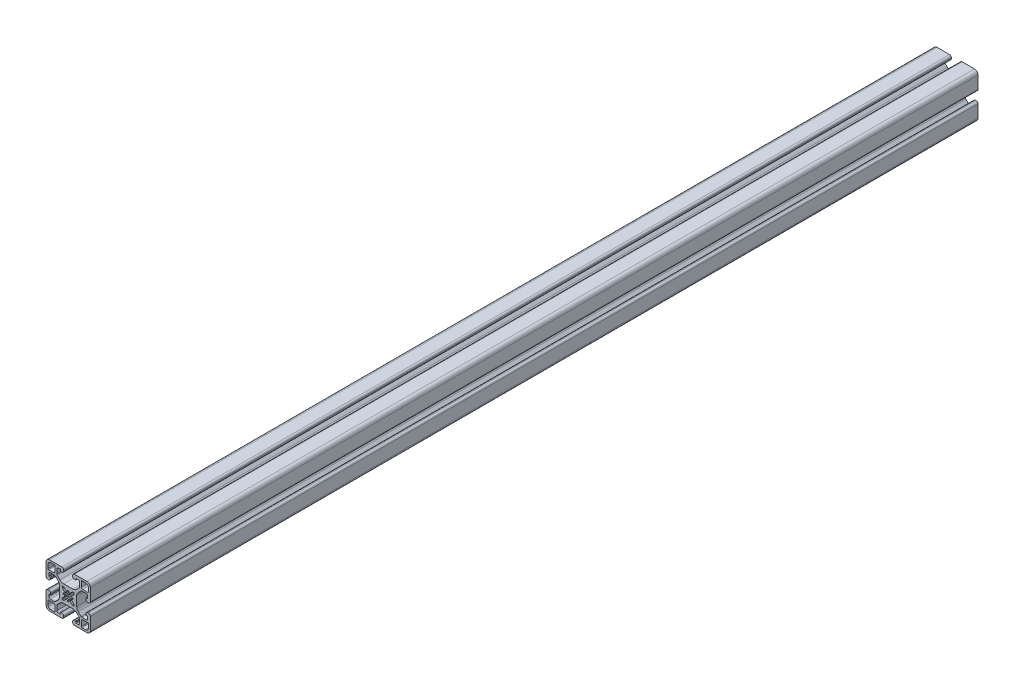
SolidWorks part; units mm, degrees
other "Extrude1"
material "6105-T5 Aluminum"
ref_plane "Front Plane" through (0, 0, 0) normal (0, 0, 1) x (1, 0, 0)
ref_plane "Top Plane" through (0, 0, 0) normal (0, 1, 0) x (1, 0, 0)
ref_plane "Right Plane" through (0, 0, 0) normal (1, 0, 0) x (0, 0, -1)
sketch "Sketch1" plane through (0, 0, 0) normal (0, 0, 1) x (1, 0, 0)
  line L0 (12.4898, -18.345) -> (15.545, -18.345)
  line L1 (11.8598, -13.1298) -> (11.8598, -17.715)
  line L2 (17.715, -11.8598) -> (13.1298, -11.8598)
  line L3 (18.345, -15.545) -> (18.345, -12.4898)
  line L4 (-18.345, -12.4898) -> (-18.345, -15.545)
  line L5 (-13.1298, -11.8598) -> (-17.715, -11.8598)
  line L6 (-11.8598, -17.715) -> (-11.8598, -13.1298)
  line L7 (-15.545, -18.345) -> (-12.4898, -18.345)
  line L8 (18.345, 12.4898) -> (18.345, 15.545)
  line L9 (13.1298, 11.8598) -> (17.715, 11.8598)
  line L10 (11.8598, 17.715) -> (11.8598, 13.1298)
  line L11 (15.545, 18.345) -> (12.4898, 18.345)
  line L12 (-12.4898, 18.345) -> (-15.545, 18.345)
  line L13 (-11.8598, 13.1298) -> (-11.8598, 17.715)
  line L14 (-17.715, 11.8598) -> (-13.1298, 11.8598)
  line L15 (-18.345, 15.545) -> (-18.345, 12.4898)
  line L16 (-5.63, 20) -> (-16.83, 20)
  line L17 (-20, 16.83) -> (-20, 5.63)
  line L18 (-18.43, 4.06) -> (-17.57, 4.06)
  line L19 (-16, 5.63) -> (-16, 6.605)
  line L20 (-16.25, 6.855) -> (-17.25, 6.855)
  line L21 (-17.5, 7.105) -> (-17.5, 9.015)
  line L22 (-16.23, 10.285) -> (-12.2162, 10.285)
  line L23 (-11.5869, 10.0243) -> (-9.0762, 7.5137)
  line L24 (-7.685, 4.1549) -> (-7.685, -4.1549)
  line L25 (-9.0762, -7.5137) -> (-11.5869, -10.0243)
  line L26 (-12.2162, -10.285) -> (-16.23, -10.285)
  line L27 (-17.5, -9.015) -> (-17.5, -7.105)
  line L28 (-17.25, -6.855) -> (-16.25, -6.855)
  line L29 (-16, -6.605) -> (-16, -5.63)
  line L30 (-17.57, -4.06) -> (-18.43, -4.06)
  line L31 (-20, -5.63) -> (-20, -16.83)
  line L32 (-16.83, -20) -> (-5.63, -20)
  line L33 (-4.06, -18.43) -> (-4.06, -17.57)
  line L34 (-5.63, -16) -> (-6.605, -16)
  line L35 (-6.855, -16.25) -> (-6.855, -17.25)
  line L36 (-7.105, -17.5) -> (-9.015, -17.5)
  line L37 (-10.285, -16.23) -> (-10.285, -12.2162)
  line L38 (-10.0243, -11.5869) -> (-7.5137, -9.0762)
  line L39 (-4.1549, -7.685) -> (4.1549, -7.685)
  line L40 (7.5137, -9.0762) -> (10.0243, -11.5869)
  line L41 (10.285, -12.2162) -> (10.285, -16.23)
  line L42 (9.015, -17.5) -> (7.105, -17.5)
  line L43 (6.855, -17.25) -> (6.855, -16.25)
  line L44 (6.605, -16) -> (5.63, -16)
  line L45 (4.06, -17.57) -> (4.06, -18.43)
  line L46 (5.63, -20) -> (16.83, -20)
  line L47 (20, -16.83) -> (20, -5.63)
  line L48 (18.43, -4.06) -> (17.57, -4.06)
  line L49 (16, -5.63) -> (16, -6.605)
  line L50 (16.25, -6.855) -> (17.25, -6.855)
  line L51 (17.5, -7.105) -> (17.5, -9.015)
  line L52 (16.23, -10.285) -> (12.2162, -10.285)
  line L53 (11.5869, -10.0243) -> (9.0762, -7.5137)
  line L54 (7.685, -4.1549) -> (7.685, 4.1549)
  line L55 (9.0762, 7.5137) -> (11.5869, 10.0243)
  line L56 (12.2162, 10.285) -> (16.23, 10.285)
  line L57 (17.5, 9.015) -> (17.5, 7.105)
  line L58 (17.25, 6.855) -> (16.25, 6.855)
  line L59 (16, 6.605) -> (16, 5.63)
  line L60 (17.57, 4.06) -> (18.43, 4.06)
  line L61 (20, 5.63) -> (20, 16.83)
  line L62 (16.83, 20) -> (5.63, 20)
  line L63 (4.06, 18.43) -> (4.06, 17.57)
  line L64 (5.63, 16) -> (6.605, 16)
  line L65 (6.855, 16.25) -> (6.855, 17.25)
  line L66 (7.105, 17.5) -> (9.015, 17.5)
  line L67 (10.285, 16.23) -> (10.285, 12.2162)
  line L68 (10.0243, 11.5869) -> (7.5137, 9.0762)
  line L69 (4.1549, 7.685) -> (-4.1549, 7.685)
  line L70 (-7.5137, 9.0762) -> (-10.0243, 11.5869)
  line L71 (-10.285, 12.2162) -> (-10.285, 16.23)
  line L72 (-9.015, 17.5) -> (-7.105, 17.5)
  line L73 (-6.855, 17.25) -> (-6.855, 16.25)
  line L74 (-6.605, 16) -> (-5.63, 16)
  line L75 (-4.06, 17.57) -> (-4.06, 18.43)
  line L76 (-4.8481, -5.4393) -> (-3.712, -5.1263)
  line L77 (-3.712, -5.1263) -> (-1.5907, -3.0049)
  line L78 (-0.625, -3.3421) -> (-0.4923, -4.0876)
  line L79 (0.4923, -4.0876) -> (0.625, -3.3421)
  line L80 (1.5907, -3.0049) -> (3.712, -5.1263)
  line L81 (3.712, -5.1263) -> (4.8481, -5.4393)
  line L82 (5.4393, -4.8481) -> (5.1263, -3.712)
  line L83 (5.1263, -3.712) -> (3.0049, -1.5907)
  line L84 (3.3421, -0.625) -> (4.0876, -0.4923)
  line L85 (4.0876, 0.4923) -> (3.3421, 0.625)
  line L86 (3.0049, 1.5907) -> (5.1263, 3.712)
  line L87 (5.1263, 3.712) -> (5.4393, 4.8481)
  line L88 (4.8481, 5.4393) -> (3.712, 5.1263)
  line L89 (3.712, 5.1263) -> (1.5907, 3.0049)
  line L90 (0.625, 3.3421) -> (0.4923, 4.0876)
  line L91 (-0.4923, 4.0876) -> (-0.625, 3.3421)
  line L92 (-1.5907, 3.0049) -> (-3.712, 5.1263)
  line L93 (-3.712, 5.1263) -> (-4.8481, 5.4393)
  line L94 (-5.4393, 4.8481) -> (-5.1263, 3.712)
  line L95 (-5.1263, 3.712) -> (-3.0049, 1.5907)
  line L96 (-3.3421, 0.625) -> (-4.0876, 0.4923)
  line L97 (-4.0876, -0.4923) -> (-3.3421, -0.625)
  line L98 (-3.0049, -1.5907) -> (-5.1263, -3.712)
  line L99 (-5.1263, -3.712) -> (-5.4393, -4.8481)
  arc A0 (15.545, -18.345) -> (18.345, -15.545) centre (15.545, -15.545) ccw
  arc A1 (11.8598, -17.715) -> (12.4898, -18.345) centre (12.4898, -17.715) ccw
  arc A2 (13.1298, -11.8598) -> (11.8598, -13.1298) centre (13.1298, -13.1298) ccw
  arc A3 (18.345, -12.4898) -> (17.715, -11.8598) centre (17.715, -12.4898) ccw
  arc A4 (-18.345, -15.545) -> (-15.545, -18.345) centre (-15.545, -15.545) ccw
  arc A5 (-17.715, -11.8598) -> (-18.345, -12.4898) centre (-17.715, -12.4898) ccw
  arc A6 (-11.8598, -13.1298) -> (-13.1298, -11.8598) centre (-13.1298, -13.1298) ccw
  arc A7 (-12.4898, -18.345) -> (-11.8598, -17.715) centre (-12.4898, -17.715) ccw
  arc A8 (18.345, 15.545) -> (15.545, 18.345) centre (15.545, 15.545) ccw
  arc A9 (17.715, 11.8598) -> (18.345, 12.4898) centre (17.715, 12.4898) ccw
  arc A10 (11.8598, 13.1298) -> (13.1298, 11.8598) centre (13.1298, 13.1298) ccw
  arc A11 (12.4898, 18.345) -> (11.8598, 17.715) centre (12.4898, 17.715) ccw
  arc A12 (-15.545, 18.345) -> (-18.345, 15.545) centre (-15.545, 15.545) ccw
  arc A13 (-11.8598, 17.715) -> (-12.4898, 18.345) centre (-12.4898, 17.715) ccw
  arc A14 (-13.1298, 11.8598) -> (-11.8598, 13.1298) centre (-13.1298, 13.1298) ccw
  arc A15 (-18.345, 12.4898) -> (-17.715, 11.8598) centre (-17.715, 12.4898) ccw
  arc A16 (-4.06, 18.43) -> (-5.63, 20) centre (-5.63, 18.43) ccw
  arc A17 (-16.83, 20) -> (-20, 16.83) centre (-16.83, 16.83) ccw
  arc A18 (-20, 5.63) -> (-18.43, 4.06) centre (-18.43, 5.63) ccw
  arc A19 (-17.57, 4.06) -> (-16, 5.63) centre (-17.57, 5.63) ccw
  arc A20 (-16, 6.605) -> (-16.25, 6.855) centre (-16.25, 6.605) ccw
  arc A21 (-17.5, 7.105) -> (-17.25, 6.855) centre (-17.25, 7.105) ccw
  arc A22 (-16.23, 10.285) -> (-17.5, 9.015) centre (-16.23, 9.015) ccw
  arc A23 (-11.5869, 10.0243) -> (-12.2162, 10.285) centre (-12.2162, 9.395) ccw
  arc A24 (-7.685, 4.1549) -> (-9.0762, 7.5137) centre (-12.435, 4.1549) ccw
  arc A25 (-9.0762, -7.5137) -> (-7.685, -4.1549) centre (-12.435, -4.1549) ccw
  arc A26 (-12.2162, -10.285) -> (-11.5869, -10.0243) centre (-12.2162, -9.395) ccw
  arc A27 (-17.5, -9.015) -> (-16.23, -10.285) centre (-16.23, -9.015) ccw
  arc A28 (-17.25, -6.855) -> (-17.5, -7.105) centre (-17.25, -7.105) ccw
  arc A29 (-16.25, -6.855) -> (-16, -6.605) centre (-16.25, -6.605) ccw
  arc A30 (-16, -5.63) -> (-17.57, -4.06) centre (-17.57, -5.63) ccw
  arc A31 (-18.43, -4.06) -> (-20, -5.63) centre (-18.43, -5.63) ccw
  arc A32 (-20, -16.83) -> (-16.83, -20) centre (-16.83, -16.83) ccw
  arc A33 (-5.63, -20) -> (-4.06, -18.43) centre (-5.63, -18.43) ccw
  arc A34 (-4.06, -17.57) -> (-5.63, -16) centre (-5.63, -17.57) ccw
  arc A35 (-6.605, -16) -> (-6.855, -16.25) centre (-6.605, -16.25) ccw
  arc A36 (-7.105, -17.5) -> (-6.855, -17.25) centre (-7.105, -17.25) ccw
  arc A37 (-10.285, -16.23) -> (-9.015, -17.5) centre (-9.015, -16.23) ccw
  arc A38 (-10.0243, -11.5869) -> (-10.285, -12.2162) centre (-9.395, -12.2162) ccw
  arc A39 (-4.1549, -7.685) -> (-7.5137, -9.0762) centre (-4.1549, -12.435) ccw
  arc A40 (7.5137, -9.0762) -> (4.1549, -7.685) centre (4.1549, -12.435) ccw
  arc A41 (10.285, -12.2162) -> (10.0243, -11.5869) centre (9.395, -12.2162) ccw
  arc A42 (9.015, -17.5) -> (10.285, -16.23) centre (9.015, -16.23) ccw
  arc A43 (6.855, -17.25) -> (7.105, -17.5) centre (7.105, -17.25) ccw
  arc A44 (6.855, -16.25) -> (6.605, -16) centre (6.605, -16.25) ccw
  arc A45 (5.63, -16) -> (4.06, -17.57) centre (5.63, -17.57) ccw
  arc A46 (4.06, -18.43) -> (5.63, -20) centre (5.63, -18.43) ccw
  arc A47 (16.83, -20) -> (20, -16.83) centre (16.83, -16.83) ccw
  arc A48 (20, -5.63) -> (18.43, -4.06) centre (18.43, -5.63) ccw
  arc A49 (17.57, -4.06) -> (16, -5.63) centre (17.57, -5.63) ccw
  arc A50 (16, -6.605) -> (16.25, -6.855) centre (16.25, -6.605) ccw
  arc A51 (17.5, -7.105) -> (17.25, -6.855) centre (17.25, -7.105) ccw
  arc A52 (16.23, -10.285) -> (17.5, -9.015) centre (16.23, -9.015) ccw
  arc A53 (11.5869, -10.0243) -> (12.2162, -10.285) centre (12.2162, -9.395) ccw
  arc A54 (7.685, -4.1549) -> (9.0762, -7.5137) centre (12.435, -4.1549) ccw
  arc A55 (9.0762, 7.5137) -> (7.685, 4.1549) centre (12.435, 4.1549) ccw
  arc A56 (12.2162, 10.285) -> (11.5869, 10.0243) centre (12.2162, 9.395) ccw
  arc A57 (17.5, 9.015) -> (16.23, 10.285) centre (16.23, 9.015) ccw
  arc A58 (17.25, 6.855) -> (17.5, 7.105) centre (17.25, 7.105) ccw
  arc A59 (16.25, 6.855) -> (16, 6.605) centre (16.25, 6.605) ccw
  arc A60 (16, 5.63) -> (17.57, 4.06) centre (17.57, 5.63) ccw
  arc A61 (18.43, 4.06) -> (20, 5.63) centre (18.43, 5.63) ccw
  arc A62 (20, 16.83) -> (16.83, 20) centre (16.83, 16.83) ccw
  arc A63 (5.63, 20) -> (4.06, 18.43) centre (5.63, 18.43) ccw
  arc A64 (4.06, 17.57) -> (5.63, 16) centre (5.63, 17.57) ccw
  arc A65 (6.605, 16) -> (6.855, 16.25) centre (6.605, 16.25) ccw
  arc A66 (7.105, 17.5) -> (6.855, 17.25) centre (7.105, 17.25) ccw
  arc A67 (10.285, 16.23) -> (9.015, 17.5) centre (9.015, 16.23) ccw
  arc A68 (10.0243, 11.5869) -> (10.285, 12.2162) centre (9.395, 12.2162) ccw
  arc A69 (4.1549, 7.685) -> (7.5137, 9.0762) centre (4.1549, 12.435) ccw
  arc A70 (-7.5137, 9.0762) -> (-4.1549, 7.685) centre (-4.1549, 12.435) ccw
  arc A71 (-10.285, 12.2162) -> (-10.0243, 11.5869) centre (-9.395, 12.2162) ccw
  arc A72 (-9.015, 17.5) -> (-10.285, 16.23) centre (-9.015, 16.23) ccw
  arc A73 (-6.855, 17.25) -> (-7.105, 17.5) centre (-7.105, 17.25) ccw
  arc A74 (-6.855, 16.25) -> (-6.605, 16) centre (-6.605, 16.25) ccw
  arc A75 (-5.63, 16) -> (-4.06, 17.57) centre (-5.63, 17.57) ccw
  arc A76 (-1.5907, -3.0049) -> (-0.625, -3.3421) centre (0, 0) ccw
  arc A77 (-0.4923, -4.0876) -> (0.4923, -4.0876) centre (0, -4) ccw
  arc A78 (0.625, -3.3421) -> (1.5907, -3.0049) centre (0, 0) ccw
  arc A79 (4.8481, -5.4393) -> (5.4393, -4.8481) centre (4.9497, -4.9497) ccw
  arc A80 (3.0049, -1.5907) -> (3.3421, -0.625) centre (0, 0) ccw
  arc A81 (4.0876, -0.4923) -> (4.0876, 0.4923) centre (4, 0) ccw
  arc A82 (3.3421, 0.625) -> (3.0049, 1.5907) centre (0, 0) ccw
  arc A83 (5.4393, 4.8481) -> (4.8481, 5.4393) centre (4.9497, 4.9497) ccw
  arc A84 (1.5907, 3.0049) -> (0.625, 3.3421) centre (0, 0) ccw
  arc A85 (0.4923, 4.0876) -> (-0.4923, 4.0876) centre (0, 4) ccw
  arc A86 (-0.625, 3.3421) -> (-1.5907, 3.0049) centre (0, 0) ccw
  arc A87 (-4.8481, 5.4393) -> (-5.4393, 4.8481) centre (-4.9497, 4.9497) ccw
  arc A88 (-3.0049, 1.5907) -> (-3.3421, 0.625) centre (0, 0) ccw
  arc A89 (-4.0876, 0.4923) -> (-4.0876, -0.4923) centre (-4, 0) ccw
  arc A90 (-3.3421, -0.625) -> (-3.0049, -1.5907) centre (0, 0) ccw
  arc A91 (-5.4393, -4.8481) -> (-4.8481, -5.4393) centre (-4.9497, -4.9497) ccw
extrude "Extrude1" add sketch "Sketch1" against normal blind 800
equation "\"0.400.00mm\"=1400"
